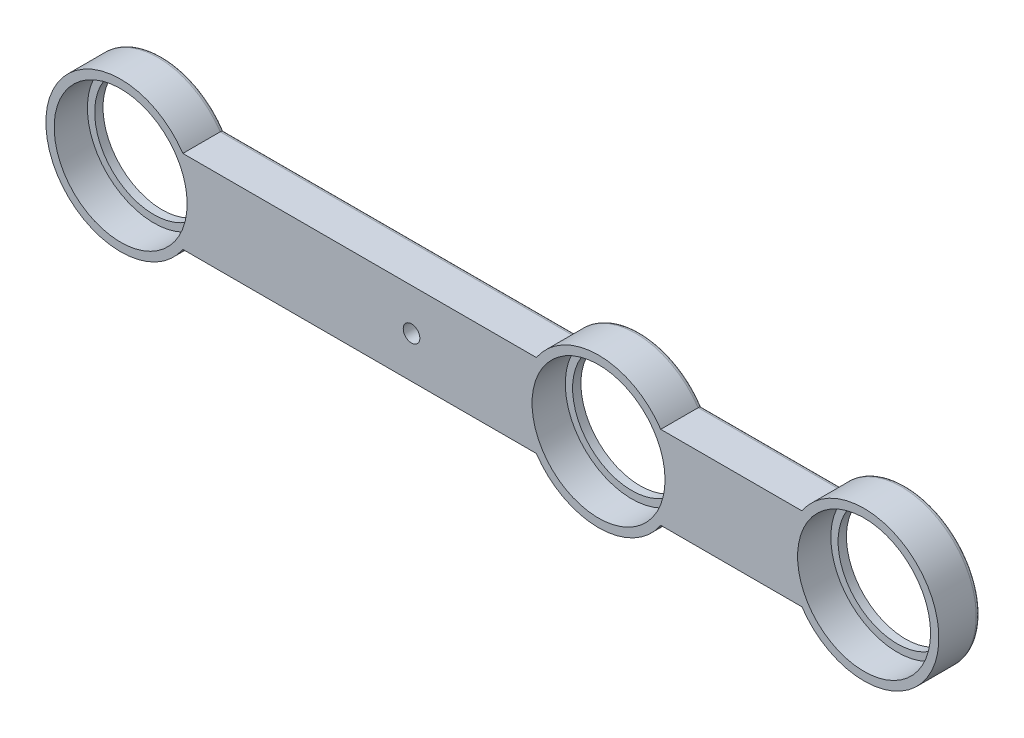
SolidWorks part; units mm, degrees
ref_plane "Plan de face" through (0, 0, 0) normal (0, 0, 1) x (1, 0, 0)
ref_plane "Plan de dessus" through (0, 0, 0) normal (0, 1, 0) x (1, 0, 0)
ref_plane "Plan de droite" through (0, 0, 0) normal (1, 0, 0) x (0, 0, -1)
sketch "Esquisse1" plane through (0, 0, 0) normal (0, 0, 1) x (1, 0, 0)
  line L0 (-100.0334, 10) -> (-14.9666, 10)
  line L1 (-100.0334, -10) -> (-14.9666, -10)
  line L2 (14.9666, -10) -> (48.9334, -10)
  line L3 (14.9666, 10) -> (48.9334, 10)
  arc A3 (-100.0334, 10) -> (-100.0334, -10) centre (-115, 0) ccw
  arc A4 (-14.9666, -10) -> (14.9666, -10) centre (0, 0) ccw
  arc A5 (48.9334, -10) -> (48.9334, 10) centre (63.9, 0) ccw
  arc A6 (14.9666, 10) -> (-14.9666, 10) centre (0, 0) ccw
  dimension "D1" = 20
  dimension "D2" = 10
  dimension "D6" = 36
  dimension "D7" = 36
  dimension "D8" = 36
  dimension "D4" = 115
  dimension "D5" = 63.9
extrude "Boss.-Extru.1" add sketch "Esquisse1" along normal blind 4
sketch "Esquisse6" plane through (0, 0, 4) normal (0, 0, 1) x (1, 0, 0)
  circle A0 centre (-115, 0) radius 16
  circle A1 centre (0, 0) radius 16
  circle A2 centre (63.9, 0) radius 16
  dimension "D1" = 32
  dimension "D2" = 32
  dimension "D3" = 32
extrude "Enlèv. mat.-Extru.1" cut sketch "Esquisse6" against normal blind 2
sketch "Esquisse7" plane through (0, 0, 2) normal (0, 0, 1) x (1, 0, 0)
  circle A0 centre (-115, 0) radius 14.25
  circle A1 centre (0, 0) radius 14.25
  circle A2 centre (63.9, 0) radius 14.25
  dimension "D1" = 28.5
  dimension "D2" = 28.5
  dimension "D3" = 28.5
extrude "Enlèv. mat.-Extru.2" cut sketch "Esquisse7" against normal through all
sketch "Esquisse10" plane through (0, 0, 4) normal (0, 0, 1) x (1, 0, 0)
  line L4 (-100.0334, -10) -> (-14.9666, -10)
  line L5 (14.9666, -10) -> (48.9334, -10)
  line L6 (48.9334, 10) -> (14.9666, 10)
  line L7 (-14.9666, 10) -> (-100.0334, 10)
  line L8 (-100.0334, -10) -> (-14.9666, -10)
  line L9 (14.9666, -10) -> (48.9334, -10)
  line L10 (48.9334, 10) -> (14.9666, 10)
  line L11 (-14.9666, 10) -> (-100.0334, 10)
  circle A0 centre (63.9, 0) radius 16 construction
  circle A1 centre (0, 0) radius 16 construction
  circle A2 centre (-115, 0) radius 16 construction
  circle A3 centre (63.9, 0) radius 16
  arc A4 (-100.0334, 10) -> (-100.0334, -10) centre (-115, 0) ccw
  arc A5 (-14.9666, -10) -> (14.9666, -10) centre (0, 0) ccw
  arc A6 (48.9334, -10) -> (48.9334, 10) centre (63.9, 0) ccw
  arc A7 (14.9666, 10) -> (-14.9666, 10) centre (0, 0) ccw
  arc A8 (-100.0334, 10) -> (-100.0334, -10) centre (-115, 0) ccw
  arc A9 (-14.9666, -10) -> (14.9666, -10) centre (0, 0) ccw
  arc A10 (48.9334, -10) -> (48.9334, 10) centre (63.9, 0) ccw
  arc A11 (14.9666, 10) -> (-14.9666, 10) centre (0, 0) ccw
  circle A12 centre (0, 0) radius 16
  circle A13 centre (-115, 0) radius 16
  dimension "D1" = 0
extrude "Boss.-Extru.5" add sketch "Esquisse10" along normal blind 6
fillet "Congé1" radius 1 8 edges at (-57.5, -10, 0) (0, -18, 0) (31.95, -10, 0) (81.9, 0, 0) (31.95, 10, 0) (0, 18, 0) (-57.5, 10, 0) (-133, 0, 0)
sketch "Esquisse12" plane through (0, 0, 0) normal (0, 0, -1) x (-1, 0, 0)
  line L0 (14.4222, -9) -> (100.5778, -9) construction
  circle A0 centre (45, 0) radius 2
  dimension "D1" = 4
  dimension "D2" = 9
  dimension "D3" = 45
extrude "Enlèv. mat.-Extru.3" cut sketch "Esquisse12" against normal through all contours A0
